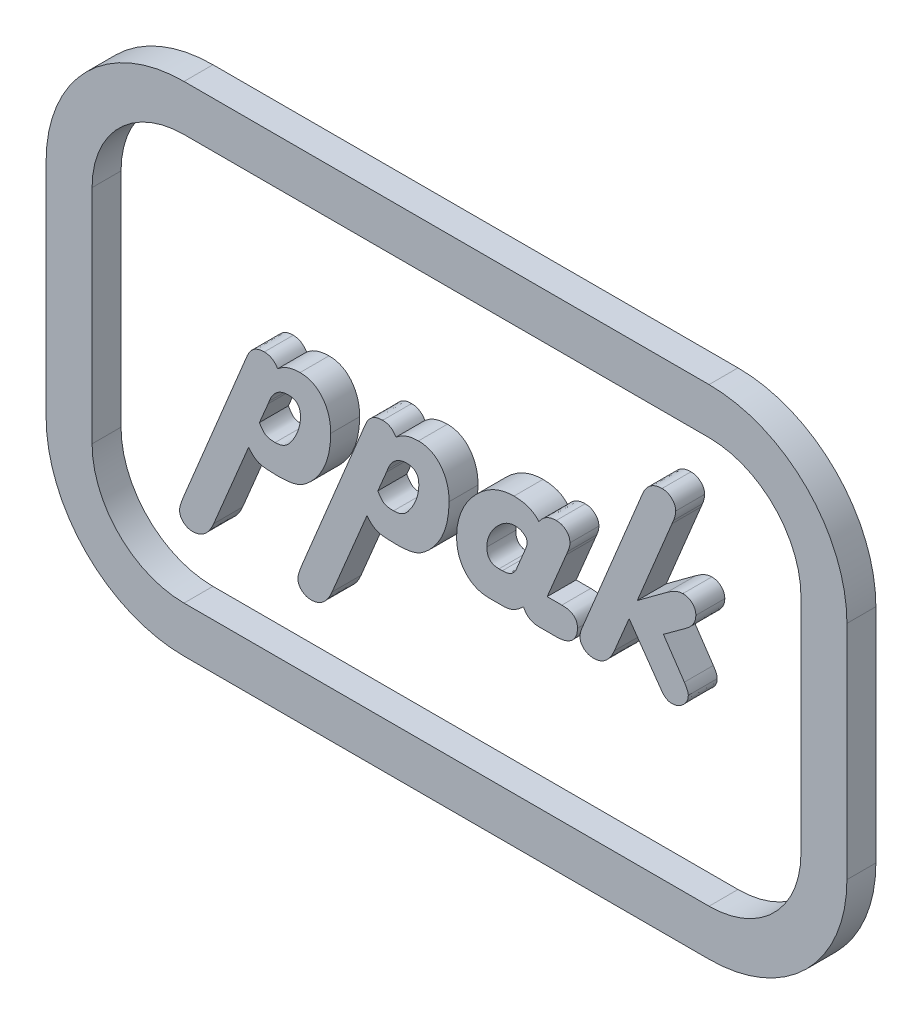
SolidWorks part; units mm, degrees
ref_plane "Front Plane" through (0, 0, 0) normal (0, 0, 1) x (1, 0, 0)
ref_plane "Top Plane" through (0, 0, 0) normal (0, 1, 0) x (1, 0, 0)
ref_plane "Right Plane" through (0, 0, 0) normal (1, 0, 0) x (0, 0, -1)
sketch "Sketch1" plane through (0, 0, 0) normal (0, 0, 1) x (1, 0, 0)
  line L0 (-10, 0) -> (10, 0) construction
  text T0 "ppak" font "Harlow Solid Italic" height 6.35
  point P4 (0, 0)
  dimension "D1" = 20
extrude "Boss-Extrude1" add sketch "Sketch1" along normal blind 1
sketch "Sketch2" plane through (0, 0, 0) normal (0, 0, 1) x (1, 0, 0)
  line L0 (0, 0) -> (0, 1.5875) construction
  line L6 (-13.8299, -2.2453) -> (-13.8299, 5.4203)
  line L7 (-9.0674, -5.4203) -> (9.0674, -5.4203)
  line L11 (-12.2424, -2.2453) -> (-12.2424, 5.4203)
  line L12 (-9.0674, 8.5953) -> (9.0674, 8.5953)
  line L13 (12.2424, -2.2453) -> (12.2424, 5.4203)
  line L14 (-12.2424, -5.4203) -> (12.2424, 8.5953) construction
  line L15 (-12.2424, 8.5953) -> (12.2424, -5.4203) construction
  line L16 (-9.0674, 10.1828) -> (9.0674, 10.1828)
  line L17 (13.8299, -2.2453) -> (13.8299, 5.4203)
  line L18 (-9.0674, -7.0078) -> (9.0674, -7.0078)
  arc A8 (9.0674, -5.4203) -> (12.2424, -2.2453) centre (9.0674, -2.2453) ccw
  arc A9 (-9.0674, -5.4203) -> (-12.2424, -2.2453) centre (-9.0674, -2.2453) cw
  arc A10 (-12.2424, 5.4203) -> (-9.0674, 8.5953) centre (-9.0674, 5.4203) cw
  arc A11 (9.0674, 8.5953) -> (12.2424, 5.4203) centre (9.0674, 5.4203) cw
  arc A12 (-13.8299, 5.4203) -> (-9.0674, 10.1828) centre (-9.0674, 5.4203) cw
  arc A13 (9.0674, 10.1828) -> (13.8299, 5.4203) centre (9.0674, 5.4203) cw
  arc A14 (9.0674, -7.0078) -> (13.8299, -2.2453) centre (9.0674, -2.2453) ccw
  arc A15 (-9.0674, -7.0078) -> (-13.8299, -2.2453) centre (-9.0674, -2.2453) cw
  dimension "D2" = 3.175
  dimension "D1" = 1.5875
  dimension "D3" = 1.5875
extrude "Boss-Extrude2" add sketch "Sketch2" along normal blind 1 separate body
